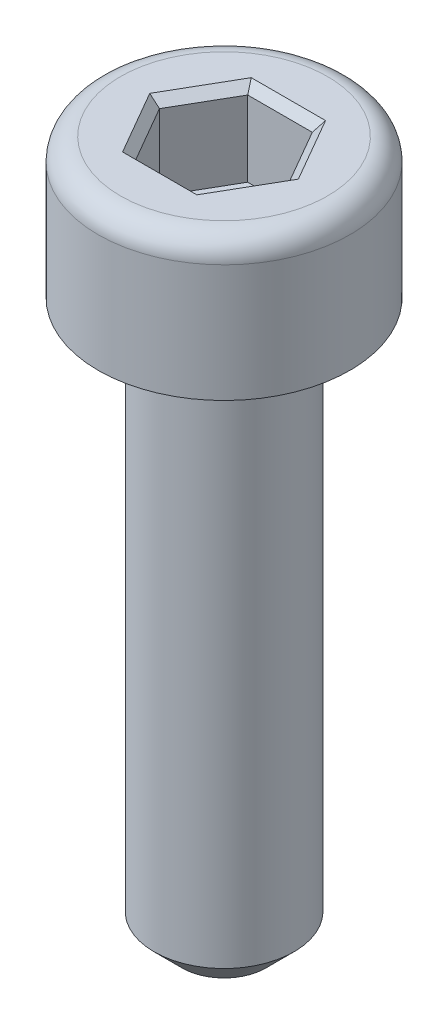
SolidWorks part; units mm, degrees
material "AISI Acier inoxydable type 316L"
ref_plane "Plan de face" through (0, 0, 0) normal (0, 0, 1) x (1, 0, 0)
ref_plane "Plan de dessus" through (0, 0, 0) normal (0, 1, 0) x (1, 0, 0)
ref_plane "Plan de droite" through (0, 0, 0) normal (1, 0, 0) x (0, 0, -1)
sketch "Esquisse1" plane through (0, 0, 0) normal (0, 0, 1) x (1, 0, 0)
  line L0 (0, 6.973) -> (0, -16.342) construction
  line L1 (1.25, -9.5) -> (0.75, -10)
  line L2 (0, 2.5) -> (1.85, 2.5)
  line L3 (2.25, 2.1) -> (2.25, 0)
  line L4 (2.25, 0) -> (1.25, 0)
  line L5 (1.25, 0) -> (1.25, -9.5)
  line L7 (0.75, -10) -> (0, -10)
  line L8 (0, -10) -> (0, 2.5)
  arc A0 (1.85, 2.5) -> (2.25, 2.1) centre (1.85, 2.1) cw
  point P9 (1.25, -10)
  point P13 (2.25, 2.5)
  dimension "D5" = 0.4
  dimension "D1" = 2.5
  dimension "D2" = 4.5
  dimension "D3" = 2.5
  dimension "D4" = 10
revolve "Révolution1" add sketch "Esquisse1" angle 360 about L0
cosmetic thread "Représentation de filetage1" parameters "D2"=1.993
sketch "Esquisse2" plane through (0, 2.5, 0) normal (0, 1, 0) x (1, 0, 0)
  line L0 (-1.1547, 0) -> (-0.5774, -1)
  line L1 (1.1547, 0) -> (0.5774, 1)
  line L2 (0.5774, 1) -> (-0.5774, 1)
  line L3 (-0.5774, 1) -> (-1.1547, 0)
  line L4 (-0.5774, -1) -> (0.5774, -1)
  line L5 (0.5774, -1) -> (1.1547, 0)
  circle A0 centre (0, 0) radius 1 construction
  dimension "D1" = 2
extrude "Enlèv. mat.-Extru.1" cut sketch "Esquisse2" against normal blind 1.5
chamfer "Chanfrein1" distance 0.15 angle 45 6 edges at (-0.866, 2.5, -0.5) (-0.866, 2.5, 0.5) (0, 2.5, 1) (0.866, 2.5, 0.5) (0.866, 2.5, -0.5) (0, 2.5, -1)
